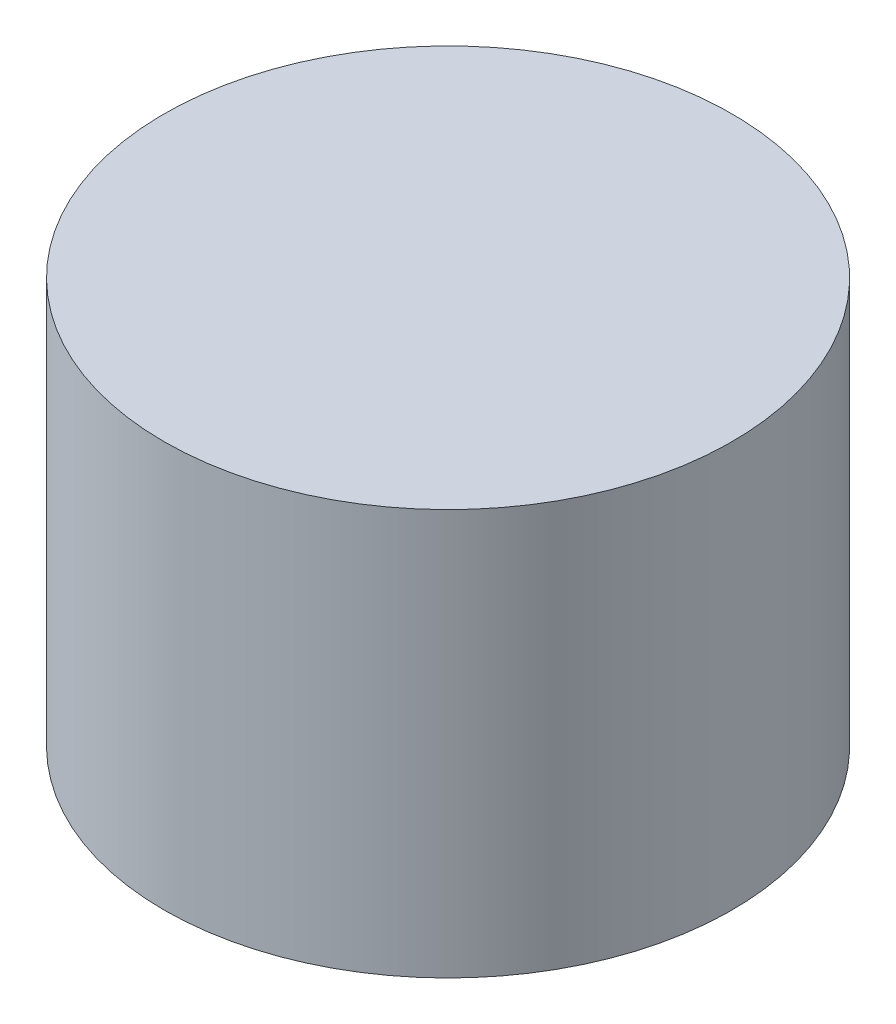
SolidWorks part; units mm, degrees
ref_plane "정면" through (0, 0, 0) normal (0, 0, 1) x (1, 0, 0)
ref_plane "윗면" through (0, 0, 0) normal (0, 1, 0) x (1, 0, 0)
ref_plane "우측면" through (0, 0, 0) normal (1, 0, 0) x (0, 0, -1)
sketch "Sketch1" plane through (0, 0, 0) normal (0, 1, 0) x (1, 0, 0)
  circle A0 centre (0, 0) radius 3.5
  dimension "D1" = 7
extrude "Boss-Extrude1" add sketch "Sketch1" along normal blind 5
